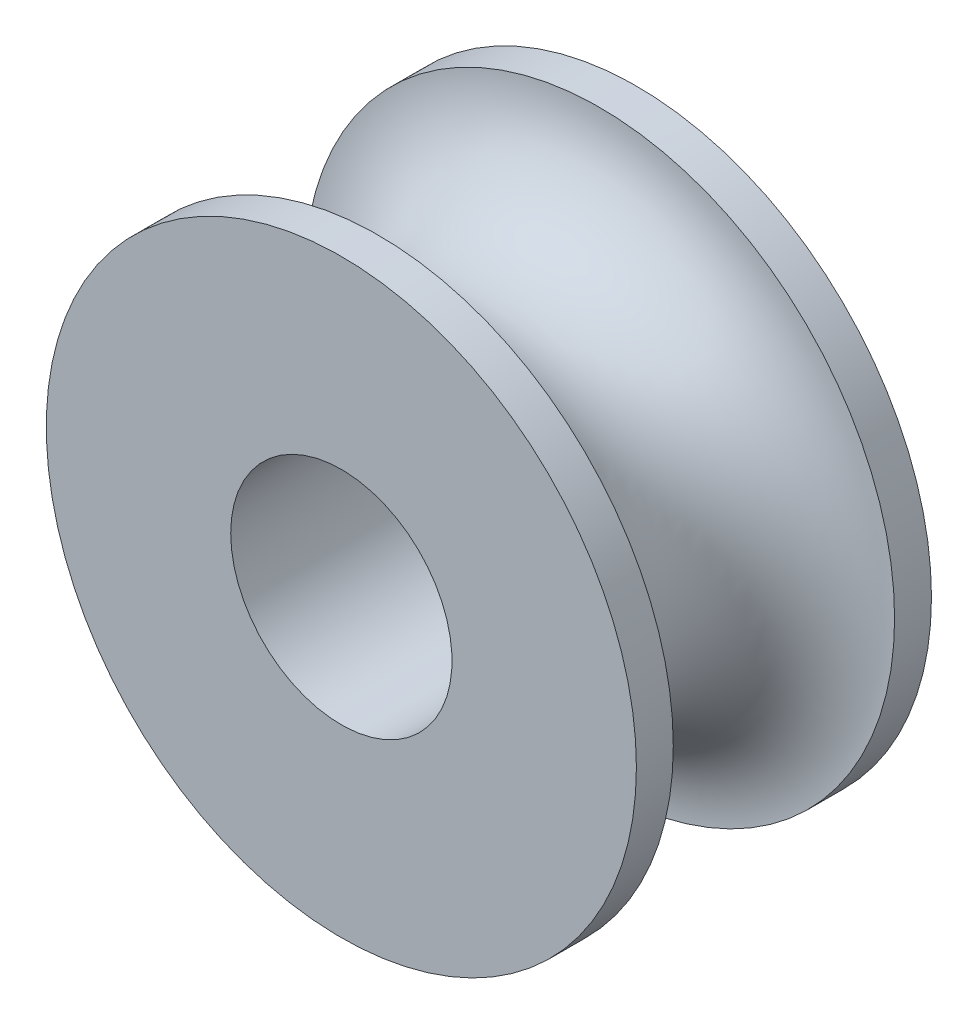
SolidWorks part; units mm, degrees
ref_plane "Front Plane" through (0, 0, 0) normal (0, 0, 1) x (1, 0, 0)
ref_plane "Top Plane" through (0, 0, 0) normal (0, 1, 0) x (1, 0, 0)
ref_plane "Right Plane" through (0, 0, 0) normal (1, 0, 0) x (0, 0, -1)
sketch "Sketch1" plane through (0, 0, 0) normal (0, 0, 1) x (1, 0, 0)
  circle A0 centre (0, 0) radius 25.4
  dimension "D1" = 50.8
extrude "Boss-Extrude1" add sketch "Sketch1" along normal blind 25.4
sketch "Sketch2" plane through (0, 0, 0) normal (0, 1, 0) x (1, 0, 0)
  line L4 (25.4, -22.225) -> (25.4, -3.175)
  line L5 (0, -32.0711) -> (0, 17.2242) construction
  arc A0 (25.4, -3.175) -> (25.4, -22.225) centre (25.4, -12.7) ccw
  dimension "D1" = 19.05
revolve "Cut-Revolve1" cut sketch "Sketch2" angle 360 about L5
sketch "Sketch3" plane through (0, 0, 0) normal (0, 0, -1) x (-1, 0, 0)
  circle A0 centre (0, 0) radius 9.525
  dimension "D1" = 19.05
extrude "Cut-Extrude1" cut sketch "Sketch3" against normal blind 25.4
